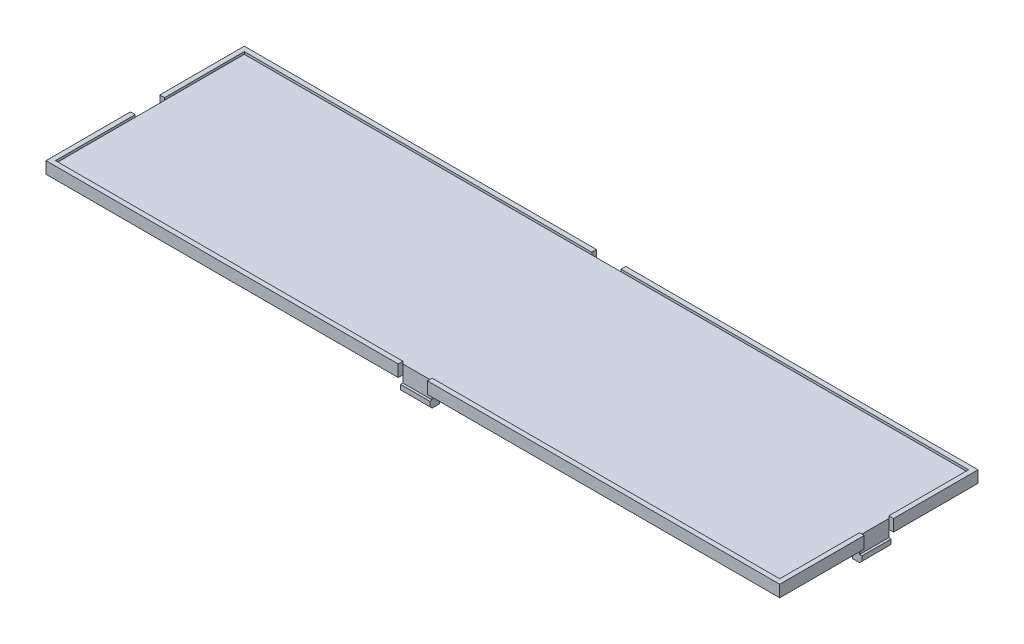
SolidWorks part; units mm, degrees
ref_plane "Спереди" through (0, 0, 0) normal (0, 0, 1) x (1, 0, 0)
ref_plane "Сверху" through (0, 0, 0) normal (0, 1, 0) x (1, 0, 0)
ref_plane "Справа" through (0, 0, 0) normal (1, 0, 0) x (0, 0, -1)
sketch "Эскиз1" plane through (0, 0, 0) normal (0, 1, 0) x (1, 0, 0)
  line L1 (77.7, -21) -> (-77.7, -21)
  line L2 (77.7, -21) -> (77.7, 21)
  line L3 (77.7, 21) -> (-77.7, 21)
  line L4 (-77.7, -21) -> (-77.7, 21)
  line L5 (77.7, -21) -> (-77.7, 21) construction
  line L6 (77.7, 21) -> (-77.7, -21) construction
  point P0 (0, 0)
  dimension "D1" = 155.4
  dimension "D2" = 42
extrude "Бобышка-Вытянуть1" add sketch "Эскиз1" along normal blind 2.5
sketch "Эскиз2" plane through (0, 2.5, 0) normal (0, 1, 0) x (1, 0, 0)
  line L0 (77.7, 21) -> (-77.7, 21) construction
  line L1 (76.7, -20) -> (-76.7, -20)
  line L2 (76.7, -20) -> (76.7, 20)
  line L3 (76.7, 20) -> (-76.7, 20)
  line L4 (-76.7, -20) -> (-76.7, 20)
  line L5 (76.7, -20) -> (-76.7, 20) construction
  line L6 (76.7, 20) -> (-76.7, -20) construction
  line L7 (-77.7, 21) -> (-77.7, -21) construction
  point P0 (0, 0)
  dimension "D1" = 1
  dimension "D2" = 1
extrude "Вырез-Вытянуть1" cut sketch "Эскиз2" against normal blind 0.5
sketch "Эскиз3" plane through (0, 2.5, 0) normal (0, 1, 0) x (1, 0, 0)
  line L0 (-77.7, 21) -> (-77.7, -21) construction
  line L1 (-77.7, 3.1) -> (-76.7, 3.1)
  line L2 (-77.7, 3.1) -> (-77.7, -3.1)
  line L3 (-77.7, -3.1) -> (-76.7, -3.1)
  line L4 (-76.7, 3.1) -> (-76.7, -3.1)
  line L5 (-76.7, 20) -> (-76.7, -20) construction
  line L6 (77.7, 21) -> (-77.7, 21) construction
  line L7 (-3.1, 21) -> (3.1, 21)
  line L8 (-3.1, 21) -> (-3.1, 20)
  line L9 (-3.1, 20) -> (3.1, 20)
  line L10 (3.1, 21) -> (3.1, 20)
  line L11 (76.7, 20) -> (-76.7, 20) construction
  line L12 (-76.7, -20) -> (76.7, -20) construction
  line L13 (-3.1, -20) -> (3.1, -20)
  line L14 (-3.1, -20) -> (-3.1, -21)
  line L15 (-3.1, -21) -> (3.1, -21)
  line L16 (3.1, -20) -> (3.1, -21)
  line L17 (-77.7, -21) -> (77.7, -21) construction
  line L18 (76.7, -20) -> (76.7, 20) construction
  line L19 (76.7, 3.1) -> (77.7, 3.1)
  line L20 (76.7, 3.1) -> (76.7, -3.1)
  line L21 (76.7, -3.1) -> (77.7, -3.1)
  line L22 (77.7, 3.1) -> (77.7, -3.1)
  line L23 (77.7, -21) -> (77.7, 21) construction
  dimension "D1" = 6.2
  dimension "D2" = 3.1
  dimension "D3" = 3.1
  dimension "D4" = 6.2
  dimension "D5" = 3.1
  dimension "D6" = 6.2
  dimension "D7" = 3.1
  dimension "D8" = 6.2
extrude "Вырез-Вытянуть2" cut sketch "Эскиз3" against normal through all
sketch "Эскиз4" plane through (0, 0, 0) normal (0, -1, 0) x (1, 0, 0)
  line L1 (-76.7, 3.1) -> (-74.7, 3.1)
  line L2 (-76.7, 3.1) -> (-76.7, -3.1)
  line L3 (-76.7, -3.1) -> (-74.7, -3.1)
  line L4 (-74.7, 3.1) -> (-74.7, -3.1)
  line L5 (-3.1, 20) -> (3.1, 20)
  line L6 (-3.1, 20) -> (-3.1, 18.5)
  line L7 (-3.1, 18.5) -> (3.1, 18.5)
  line L8 (3.1, 20) -> (3.1, 18.5)
  line L9 (-3.1, -20) -> (3.1, -20)
  line L10 (-3.1, -20) -> (-3.1, -18.5)
  line L11 (-3.1, -18.5) -> (3.1, -18.5)
  line L12 (3.1, -20) -> (3.1, -18.5)
  line L13 (76.7, 3.1) -> (75.2, 3.1)
  line L14 (76.7, 3.1) -> (76.7, -3.1)
  line L15 (76.7, -3.1) -> (75.2, -3.1)
  line L16 (75.2, 3.1) -> (75.2, -3.1)
  dimension "D1" = 2
  dimension "D2" = 6.2
  dimension "D3" = 1.5
  dimension "D4" = 6.2
  dimension "D5" = 1.5
  dimension "D6" = 6.2
  dimension "D7" = 1.5
  dimension "D8" = 6.2
extrude "Бобышка-Вытянуть2" add sketch "Эскиз4" along normal blind 3
sketch "Эскиз6" plane through (0, 0, 3.1) normal (0, 0, 1) x (1, 0, 0)
  line L0 (-76.7, -3) -> (-77.2, -2.5)
  line L1 (-77.2, -2.5) -> (-77.2, -1.5)
  line L2 (-77.2, -1.5) -> (-76.6, -1.5)
  line L3 (-76.6, -1.5) -> (-76.6, -3)
  line L4 (-74.7, -3) -> (-76.7, -3) construction
  line L5 (-76.6, -3) -> (-76.7, -3)
  line L6 (-76.7, -3) -> (-76.7, 0) construction
  line L7 (-77.7, 0) -> (-3.1, 0) construction
  dimension "D1" = 0.5
  dimension "D2" = 0.1
  dimension "D3" = 1.5
  dimension "D4" = 1
extrude "Бобышка-Вытянуть3" add sketch "Эскиз6" against normal blind 6.2
mirror "Зеркальное отражение1" about plane through (0, 0, 0) normal (1, 0, 0) of "Бобышка-Вытянуть3"
sketch "Эскиз8" plane through (3.1, 0, 0) normal (1, 0, 0) x (0, 0, -1)
  line L0 (-20, -3) -> (-20.5, -2.5)
  line L1 (-20.5, -2.5) -> (-20.5, -1.5)
  line L2 (-20.5, -1.5) -> (-19.9, -1.5)
  line L3 (-19.9, -1.5) -> (-19.9, -3)
  line L4 (-18.5, -3) -> (-20, -3) construction
  line L5 (-19.9, -3) -> (-20, -3)
  line L6 (-20, -3) -> (-20, 0) construction
  line L7 (-21, 0) -> (-3.1, 0) construction
  dimension "D1" = 0.1
  dimension "D2" = 1.5
  dimension "D3" = 1
  dimension "D4" = 0.5
extrude "Бобышка-Вытянуть4" add sketch "Эскиз8" against normal blind 6.2
mirror "Зеркальное отражение2" about plane through (0, 0, 0) normal (0, 0, 1) of "Бобышка-Вытянуть4"
